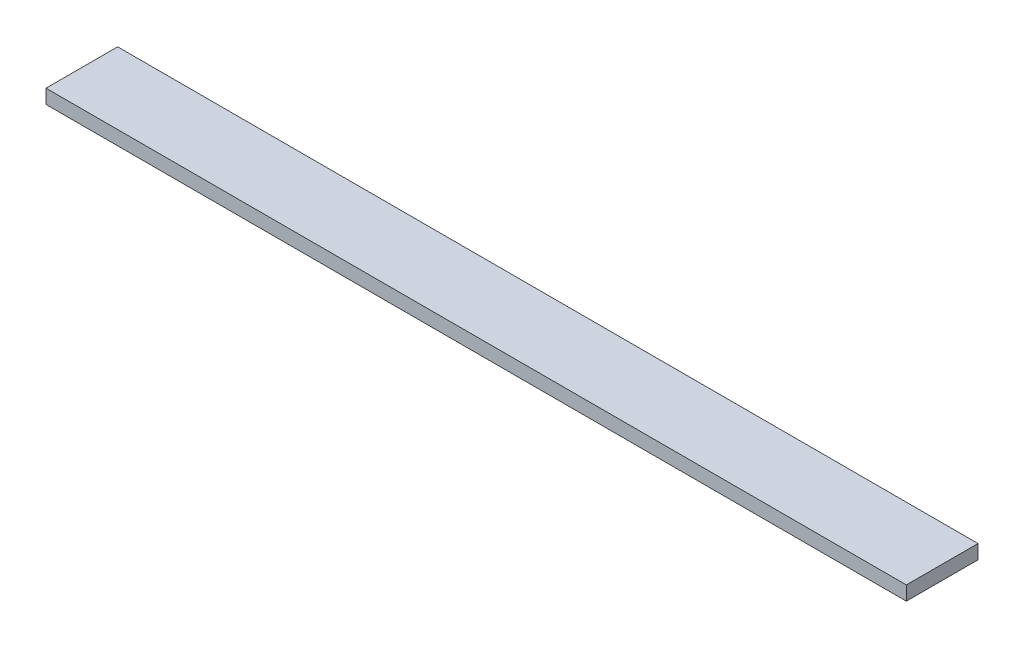
SolidWorks part; units mm, degrees
material "6061-T4 (SS)"
ref_plane "Front Plane" through (0, 0, 0) normal (0, 0, 1) x (1, 0, 0)
ref_plane "Top Plane" through (0, 0, 0) normal (0, 1, 0) x (1, 0, 0)
ref_plane "Right Plane" through (0, 0, 0) normal (1, 0, 0) x (0, 0, -1)
sketch "Sketch1" plane through (0, 0, 0) normal (1, 0, 0) x (0, 0, -1)
  line L1 (-12.7, -2.5) -> (12.7, -2.5)
  line L2 (-12.7, -2.5) -> (-12.7, 2.5)
  line L3 (-12.7, 2.5) -> (12.7, 2.5)
  line L4 (12.7, -2.5) -> (12.7, 2.5)
  line L5 (-12.7, -2.5) -> (12.7, 2.5) construction
  line L6 (-12.7, 2.5) -> (12.7, -2.5) construction
  point P0 (0, 0)
  dimension "D1" = 25.4
  dimension "D2" = 5
extrude "Boss-Extrude1" add sketch "Sketch1" along normal blind 305
sketch "Sketch2" plane through (0, -2.5, 0) normal (0, -1, 0) x (1, 0, 0)
  line L0 (0, 0) -> (305, 0) construction
  line L1 (52.5, -5) -> (252.5, -5)
  line L2 (52.5, -5) -> (52.5, 5)
  line L3 (52.5, 5) -> (252.5, 5)
  line L4 (252.5, -5) -> (252.5, 5)
  line L5 (52.5, -5) -> (252.5, 5) construction
  line L6 (52.5, 5) -> (252.5, -5) construction
  line L8 (305, 12.7) -> (305, -12.7) construction
  point P0 (152.5, 0)
  dimension "D1" = 10
  dimension "D2" = 200
extrude "Boss-Extrude2" add sketch "Sketch2" along normal blind 0.5 separate body
